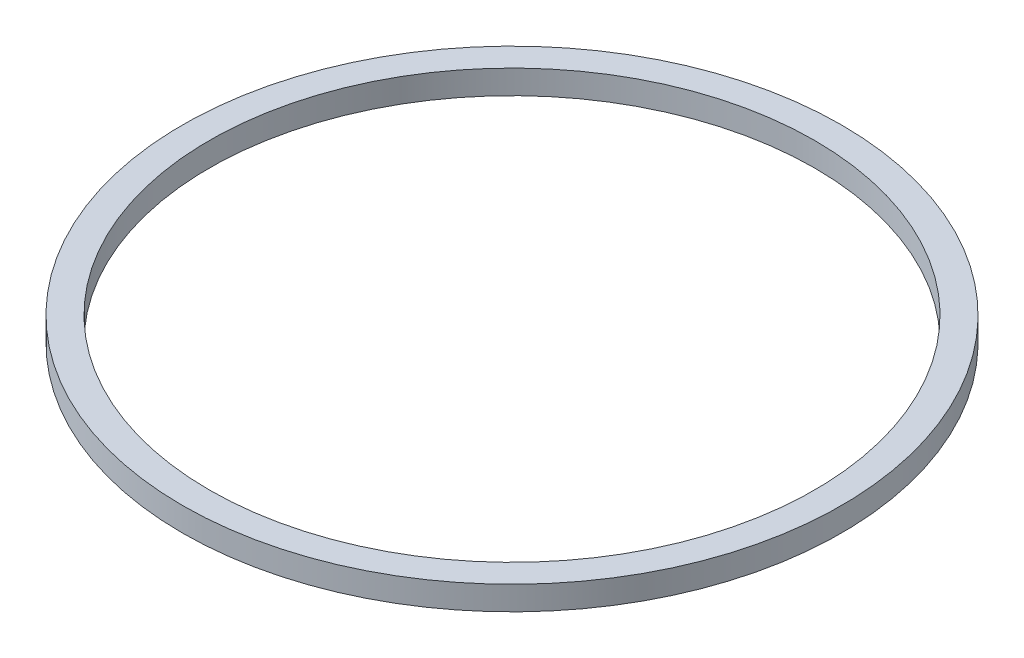
SolidWorks part; units mm, degrees
material "6061 Alloy"
ref_plane "Front Plane" through (0, 0, 0) normal (0, 0, 1) x (1, 0, 0)
ref_plane "Top Plane" through (0, 0, 0) normal (0, 1, 0) x (1, 0, 0)
ref_plane "Right Plane" through (0, 0, 0) normal (1, 0, 0) x (0, 0, -1)
sketch "Sketch1" plane through (0, 0, 0) normal (0, 1, 0) x (1, 0, 0)
  circle A0 centre (0, 0) radius 80.391
  circle A1 centre (0, 0) radius 87.5284
  dimension "D1" = 160.782
  dimension "D2" = 175.0568
extrude "Boss-Extrude1" add sketch "Sketch1" along normal blind 6.35
